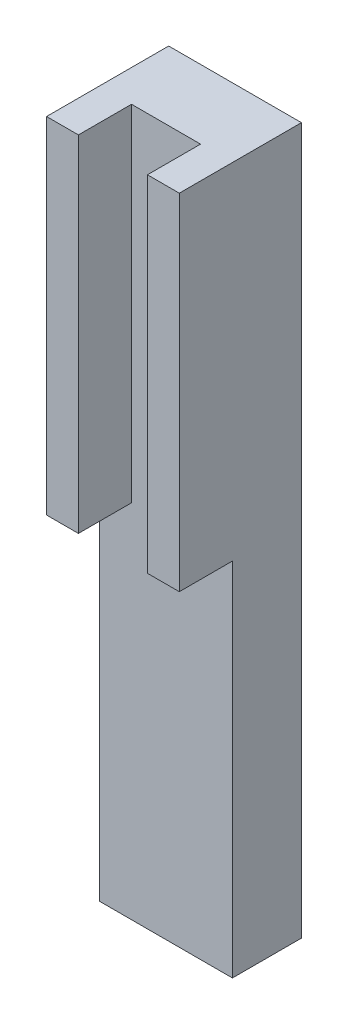
SolidWorks part; units mm, degrees
ref_plane "Front Plane" through (0, 0, 0) normal (0, 0, 1) x (1, 0, 0)
ref_plane "Top Plane" through (0, 0, 0) normal (0, 1, 0) x (1, 0, 0)
ref_plane "Right Plane" through (0, 0, 0) normal (1, 0, 0) x (0, 0, -1)
sketch "Sketch1" plane through (0, 0, 0) normal (0, 0, 1) x (1, 0, 0)
  line L0 (0, 0) -> (0, 132.9995)
  line L1 (0, 132.9995) -> (25.0012, 132.9995)
  line L2 (25.0012, 132.9995) -> (25.0012, 0)
  line L3 (25.0012, 0) -> (0, 0)
  dimension "D1" = 132.9995
  dimension "D2" = 25.0012
extrude "Boss-Extrude1" add sketch "Sketch1" along normal blind 22.9997
sketch "Sketch2" plane through (0, 0, 22.9997) normal (0, 0, 1) x (1, 0, 0)
  line L0 (0, 0) -> (0, 68.0009)
  line L1 (0, 132.9995) -> (0, 0) construction
  line L2 (0, 68.0009) -> (25.0012, 68.0009)
  line L3 (25.0012, 0) -> (25.0012, 132.9995) construction
  line L4 (25.0012, 68.0009) -> (25.0012, 0)
  line L5 (25.0012, 0) -> (0, 0)
  dimension "D1" = 68.0009
extrude "Cut-Extrude1" cut sketch "Sketch2" against normal blind 10
sketch "Sketch3" plane through (0, 0, 22.9997) normal (0, 0, 1) x (1, 0, 0)
  line L0 (5.9995, 68.0009) -> (5.9995, 132.9995)
  line L1 (25.0012, 68.0009) -> (0, 68.0009) construction
  line L2 (25.0012, 132.9995) -> (0, 132.9995) construction
  line L3 (5.9995, 132.9995) -> (19.0017, 132.9995)
  line L4 (19.0017, 132.9995) -> (19.0017, 68.0009)
  line L5 (19.0017, 68.0009) -> (5.9995, 68.0009)
  line L6 (0, 132.9995) -> (0, 68.0009) construction
  line L7 (25.0012, 68.0009) -> (25.0012, 132.9995) construction
  dimension "D1" = 5.9995
  dimension "D2" = 5.9995
extrude "Cut-Extrude2" cut sketch "Sketch3" against normal blind 10
